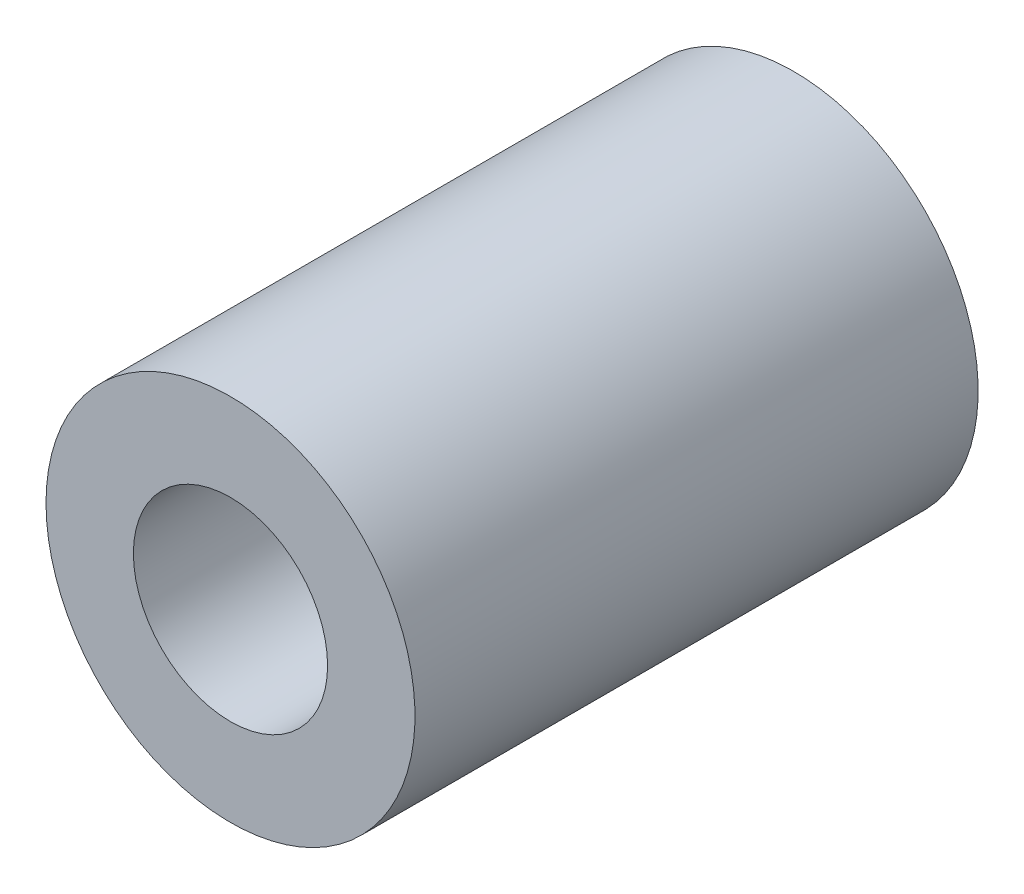
SolidWorks part; units mm, degrees
ref_plane "前视基准面" through (0, 0, 0) normal (0, 0, 1) x (1, 0, 0)
ref_plane "上视基准面" through (0, 0, 0) normal (0, 1, 0) x (1, 0, 0)
ref_plane "右视基准面" through (0, 0, 0) normal (1, 0, 0) x (0, 0, -1)
sketch "草图1" plane through (0, 0, 0) normal (0, 0, 1) x (1, 0, 0)
  circle A0 centre (0, 0) radius 9.5
  circle A1 centre (0, 0) radius 5
  dimension "D1" = 10
  dimension "D2" = 19
extrude "凸台-拉伸1" add sketch "草图1" along normal mid plane 29
